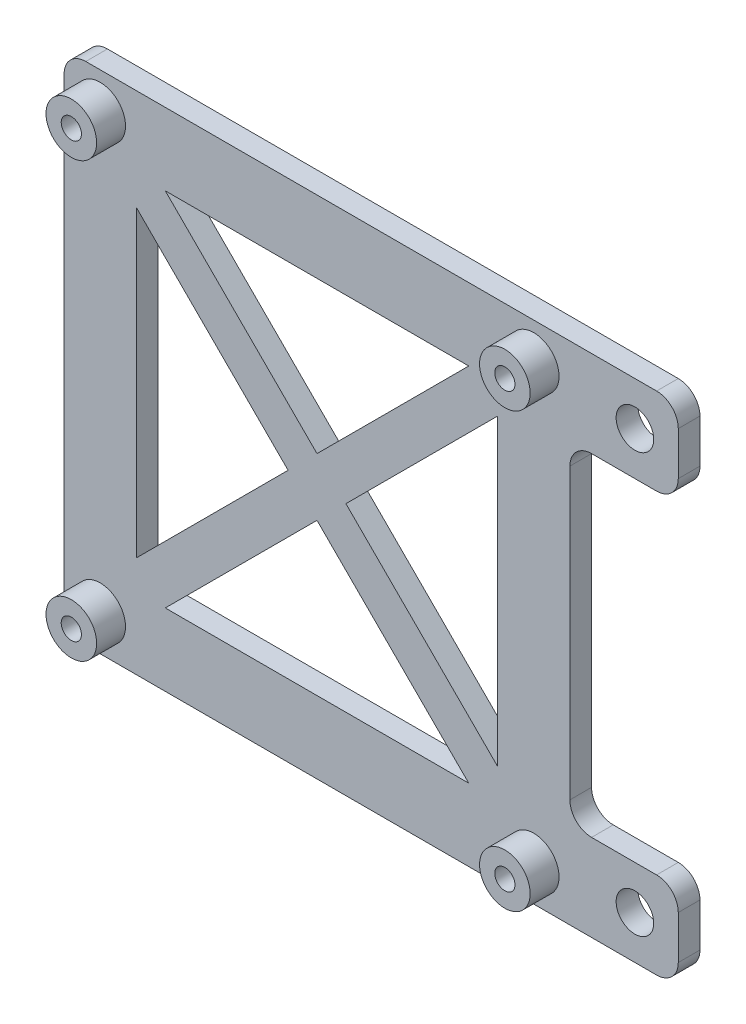
SolidWorks part; units mm, degrees
ref_plane "Front Plane" through (0, 0, 0) normal (0, 0, 1) x (1, 0, 0)
ref_plane "Top Plane" through (0, 0, 0) normal (0, 1, 0) x (1, 0, 0)
ref_plane "Right Plane" through (0, 0, 0) normal (1, 0, 0) x (0, 0, -1)
sketch "Sketch1" plane through (0, 0, 0) normal (0, 0, 1) x (1, 0, 0)
  line L1 (3, 0) -> (70, 0)
  line L2 (0, 3) -> (0, 67)
  line L3 (3, 70) -> (67, 70)
  line L4 (70, 15) -> (70, 55)
  line L5 (67, 70) -> (82, 70)
  line L7 (73, 58) -> (82, 58)
  line L8 (85, 67) -> (85, 61)
  line L9 (70, 0) -> (82, 0)
  line L11 (73, 12) -> (82, 12)
  line L12 (85, 3) -> (85, 9)
  arc A0 (3, 70) -> (0, 67) centre (3, 67) ccw
  arc A1 (0, 3) -> (3, 0) centre (3, 3) ccw
  arc A2 (85, 3) -> (82, 0) centre (82, 3) cw
  arc A3 (85, 9) -> (82, 12) centre (82, 9) ccw
  arc A4 (73, 12) -> (70, 15) centre (73, 15) cw
  arc A5 (82, 70) -> (85, 67) centre (82, 67) cw
  arc A6 (85, 61) -> (82, 58) centre (82, 61) cw
  arc A7 (73, 58) -> (70, 55) centre (73, 55) ccw
  circle A8 centre (79, 64) radius 2.6
  circle A9 centre (79, 6) radius 2.6
  point P13 (0, 70)
  point P16 (0, 0)
  point P25 (85, 70)
  point P28 (85, 58)
  point P31 (85, 64)
  point P36 (0, 0)
  point P37 (0, 0)
  point P38 (85, 6)
  point P39 (0, 0)
  dimension "D4" = 3
  dimension "D6" = 5.2
  dimension "D1" = 70
  dimension "D2" = 15
  dimension "D3" = 12
  dimension "D5" = 70
  dimension "D7" = 6
  dimension "D8" = 9
extrude "Boss-Extrude1" add sketch "Sketch1" along normal blind 3
sketch "Sketch2" plane through (0, 0, 3) normal (0, 0, 1) x (1, 0, 0)
  line L0 (0, 67) -> (0, 3) construction
  line L1 (5, 65) -> (65, 65) construction
  line L2 (5, 65) -> (5, 5) construction
  line L3 (5, 5) -> (65, 5) construction
  line L4 (65, 65) -> (65, 5) construction
  line L5 (0, 67) -> (0, 3) construction
  circle A0 centre (5, 65) radius 3.5
  circle A1 centre (65, 65) radius 3.5
  circle A2 centre (65, 5) radius 3.5
  circle A3 centre (5, 5) radius 3.5
  point P6 (0, 35)
  point P7 (5, 35)
  dimension "D3" = 7
  dimension "D1" = 60
  dimension "D2" = 5
extrude "Boss-Extrude2" add sketch "Sketch2" along normal blind 4
sketch "Sketch3" plane through (0, 0, 3) normal (0, 0, 1) x (1, 0, 0)
  line L0 (14, 60) -> (56, 60)
  line L5 (35, 39) -> (35, 35) construction
  line L6 (56, 60) -> (35, 39)
  line L19 (35, 39) -> (14, 60)
  line L20 (82, 70) -> (3, 70) construction
  line L21 (0, 67) -> (0, 3) construction
  line L22 (60, 56) -> (60, 14)
  line L23 (70, 15) -> (70, 55) construction
  line L24 (39, 35) -> (60, 56)
  line L25 (60, 14) -> (39, 35)
  line L26 (56, 10) -> (14, 10)
  line L27 (35, 31) -> (56, 10)
  line L28 (14, 10) -> (35, 31)
  line L29 (10, 14) -> (10, 56)
  line L30 (31, 35) -> (10, 14)
  line L31 (10, 56) -> (31, 35)
  point P5 (0, 35)
  point P6 (35, 60)
  point P24 (35, 35)
  dimension "D1" = 10
  dimension "D2" = 14
  dimension "D3" = 14
  dimension "D4" = 4
  dimension "D5" = 4
extrude "Cut-Extrude1" cut sketch "Sketch3" against normal blind 3
sketch "Sketch4" plane through (0, 0, 7) normal (0, 0, 1) x (1, 0, 0)
  circle A0 centre (5, 65) radius 1.4
  circle A1 centre (65, 65) radius 1.4
  circle A2 centre (65, 5) radius 1.4
  circle A3 centre (5, 5) radius 1.4
  dimension "D1" = 2.8
extrude "Cut-Extrude2" cut sketch "Sketch4" against normal through all
